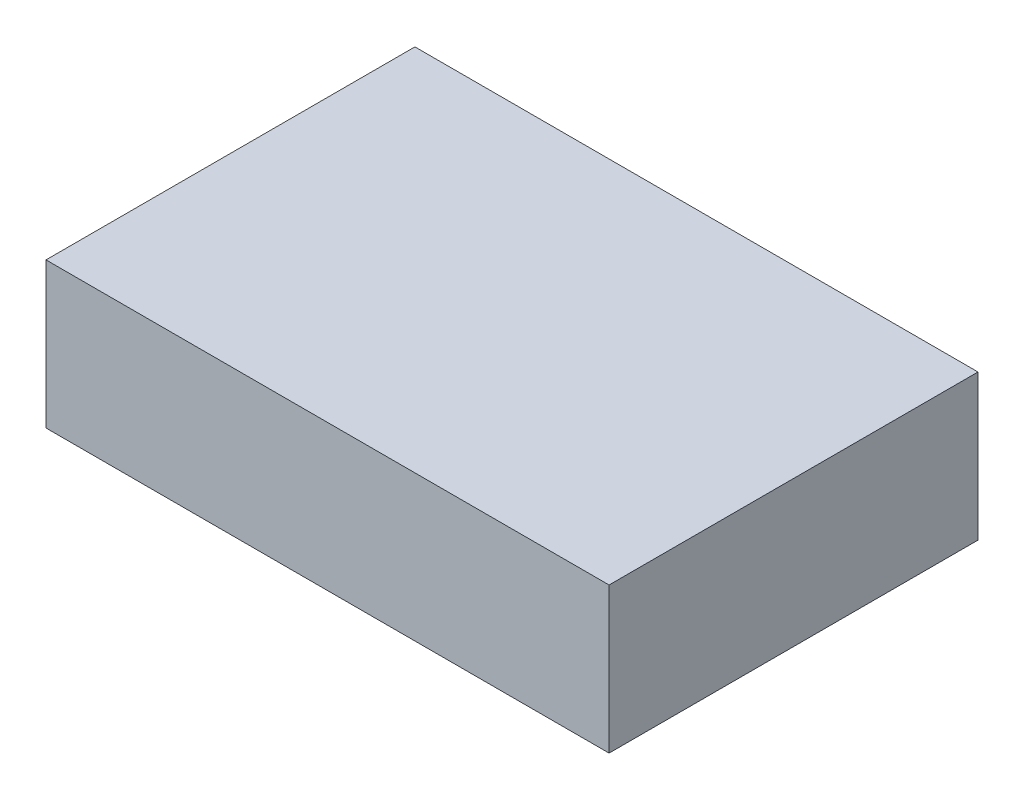
SolidWorks part; units mm, degrees
material "Corrugated Paper"
ref_plane "Front Plane" through (0, 0, 0) normal (0, 0, 1) x (1, 0, 0)
ref_plane "Top Plane" through (0, 0, 0) normal (0, 1, 0) x (1, 0, 0)
ref_plane "Right Plane" through (0, 0, 0) normal (1, 0, 0) x (0, 0, -1)
sketch "Sketch1" plane through (0, 0, 0) normal (0, 1, 0) x (1, 0, 0)
  line L1 (0, 0) -> (58, 0)
  line L2 (0, 0) -> (0, -38)
  line L3 (0, -38) -> (58, -38)
  line L4 (58, 0) -> (58, -38)
  dimension "D1" = 58
  dimension "D2" = 38
extrude "Boss-Extrude1" add sketch "Sketch1" along normal blind 15
